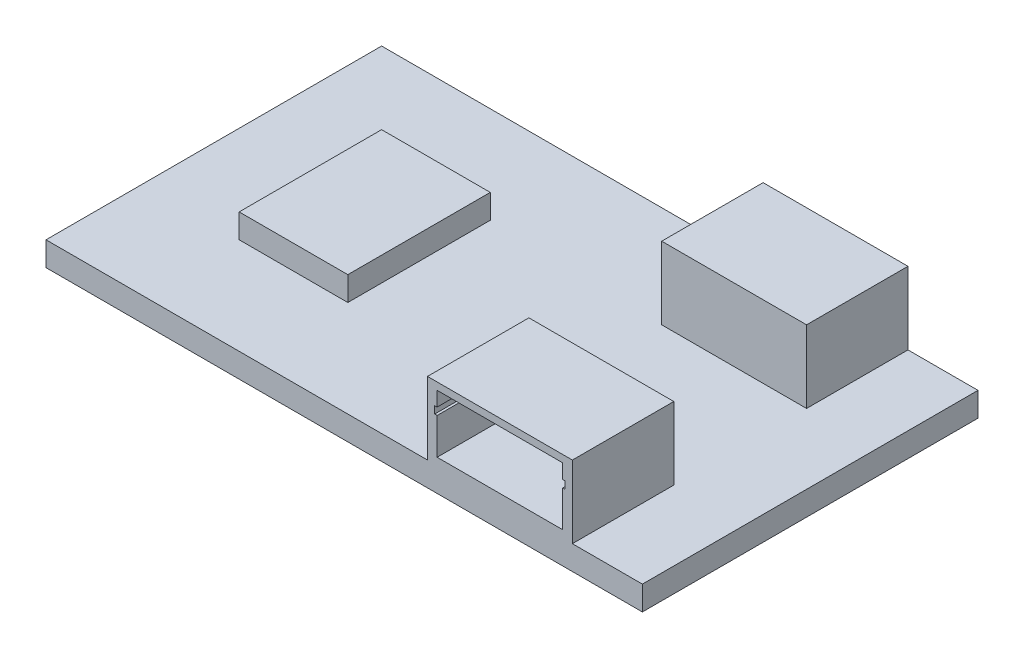
SolidWorks part; units mm, degrees
ref_plane "Front" through (0, 0, 0) normal (0, 0, 1) x (1, 0, 0)
ref_plane "Top" through (0, 0, 0) normal (0, 1, 0) x (1, 0, 0)
ref_plane "Right" through (0, 0, 0) normal (1, 0, 0) x (0, 0, -1)
sketch "Sketch1" plane through (0, 0, 0) normal (0, 1, 0) x (1, 0, 0)
  line L1 (-12.35, 6.95) -> (12.35, 6.95)
  line L2 (-12.35, 6.95) -> (-12.35, -6.95)
  line L3 (-12.35, -6.95) -> (12.35, -6.95)
  line L4 (12.35, 6.95) -> (12.35, -6.95)
  line L5 (-12.35, 6.95) -> (12.35, -6.95) construction
  line L6 (-12.35, -6.95) -> (12.35, 6.95) construction
  point P0 (0, 0)
  dimension "D1" = 24.7
  dimension "D2" = 13.9
extrude "Boss-Extrude1" add sketch "Sketch1" along normal blind 1
sketch "Sketch2" plane through (0, 1, 0) normal (0, 1, 0) x (1, 0, 0)
  line L0 (9.45, -6.95) -> (3.45, -6.95)
  line L1 (9.45, -6.95) -> (9.45, -2.75)
  line L2 (3.45, -6.95) -> (3.45, -2.75)
  line L3 (9.45, -2.75) -> (3.45, -2.75)
  line L4 (-12.35, -6.95) -> (12.35, -6.95) construction
  line L5 (12.35, -6.95) -> (12.35, 6.95) construction
  line L6 (-12.35, 0) -> (12.35, 0) construction
  line L7 (-12.35, 6.95) -> (-12.35, -6.95) construction
  line L8 (9.45, 6.95) -> (9.45, 2.75)
  line L9 (9.45, 6.95) -> (3.45, 6.95)
  line L10 (3.45, 6.95) -> (3.45, 2.75)
  line L11 (9.45, 2.75) -> (3.45, 2.75)
  dimension "D1" = 2.9
  dimension "D2" = 4.2
  dimension "D3" = 6
extrude "Boss-Extrude2" add sketch "Sketch2" along normal blind 3
sketch "Sketch3" plane through (0, 0, 6.95) normal (0, 0, 1) x (1, 0, 0)
  line L0 (3.85, 3.7) -> (3.85, 3.1)
  line L1 (3.85, 3.1) -> (3.75, 3.1)
  line L2 (3.75, 3.1) -> (3.75, 2.8)
  line L3 (3.75, 2.8) -> (3.85, 2.8)
  line L4 (3.85, 2.8) -> (3.85, 1.3)
  line L5 (6.45, 4) -> (6.45, 0) construction
  line L6 (3.45, 4) -> (9.45, 4) construction
  line L7 (-12.35, 0) -> (12.35, 0) construction
  line L8 (3.85, 1.3) -> (9.05, 1.3)
  line L10 (9.05, 3.7) -> (3.85, 3.7)
  line L11 (3.45, 4) -> (3.45, 1) construction
  line L12 (-12.35, 1) -> (3.45, 1) construction
  line L13 (9.05, 2.8) -> (9.05, 1.3)
  line L14 (9.15, 2.8) -> (9.05, 2.8)
  line L15 (9.15, 3.1) -> (9.15, 2.8)
  line L16 (9.05, 3.1) -> (9.15, 3.1)
  line L17 (9.05, 3.7) -> (9.05, 3.1)
  line L18 (3.45, 1) -> (9.45, 1) construction
  dimension "D1" = 0.3
  dimension "D2" = 0.3
  dimension "D3" = 0.1
  dimension "D4" = 0.1
  dimension "D5" = 0.3
  dimension "D6" = 0.6
  dimension "D7" = 0.3
sketch "Sketch4" plane through (0, 1, 0) normal (0, 1, 0) x (1, 0, 0)
  line L0 (-12.35, 0) -> (12.35, 0) construction
  line L1 (-12.35, 6.95) -> (-12.35, -6.95) construction
  line L2 (12.35, -6.95) -> (12.35, 6.95) construction
extrude "Cut-Extrude1" cut sketch "Sketch3" against normal blind 3
sketch "Sketch5" plane through (0, 0, -6.95) normal (0, 0, -1) x (-1, 0, 0)
  line L0 (-9.15, 3.7) -> (-9.15, 3.1)
  line L1 (-9.15, 3.1) -> (-9.25, 3.1)
  line L2 (-9.25, 3.1) -> (-9.25, 2.8)
  line L3 (-9.25, 2.8) -> (-9.15, 2.8)
  line L4 (-9.15, 2.8) -> (-9.15, 1.3)
  line L5 (-6.5592, -5.0038) -> (-6.5592, -1.7799) construction
  line L14 (-9.45, 4) -> (-9.45, 1) construction
  line L15 (-6.45, 4) -> (-6.45, 1) construction
  line L18 (-9.45, 4) -> (-3.45, 4) construction
  line L19 (12.35, 1) -> (-12.35, 1) construction
  line L20 (-9.15, 3.7) -> (-3.75, 3.7)
  line L22 (-3.75, 1.3) -> (-9.15, 1.3)
  line L23 (-3.75, 3.7) -> (-3.75, 3.1)
  line L24 (-3.75, 3.1) -> (-3.65, 3.1)
  line L25 (-3.65, 3.1) -> (-3.65, 2.8)
  line L26 (-3.65, 2.8) -> (-3.75, 2.8)
  line L27 (-3.75, 2.8) -> (-3.75, 1.3)
  point P21 (-9.25, 2.95)
  dimension "D1" = 0.3
  dimension "D2" = 0.3
  dimension "D3" = 0.3
  dimension "D4" = 0.1
  dimension "D5" = 0.3
  dimension "D6" = 0.3
extrude "Cut-Extrude2" cut sketch "Sketch5" against normal blind 3
sketch "Sketch6" plane through (0, 1, 0) normal (0, 1, 0) x (1, 0, 0)
  line L0 (-12.35, 6.95) -> (-12.35, -6.95) construction
  line L1 (-8.35, 2.95) -> (-3.85, 2.95)
  line L2 (-8.35, 2.95) -> (-8.35, -2.95)
  line L3 (-8.35, -2.95) -> (-3.85, -2.95)
  line L4 (-3.85, 2.95) -> (-3.85, -2.95)
  line L5 (-8.35, 2.95) -> (-3.85, -2.95) construction
  line L6 (-8.35, -2.95) -> (-3.85, 2.95) construction
  line L7 (3.45, 6.95) -> (-12.35, 6.95) construction
  line L8 (-12.35, -6.95) -> (3.45, -6.95) construction
  point P0 (-6.1, 0)
  point P9 (-6.1, 2.95)
  dimension "D1" = 4
  dimension "D2" = 4
  dimension "D3" = 4
  dimension "D4" = 4.5
extrude "Boss-Extrude3" add sketch "Sketch6" along normal blind 1
